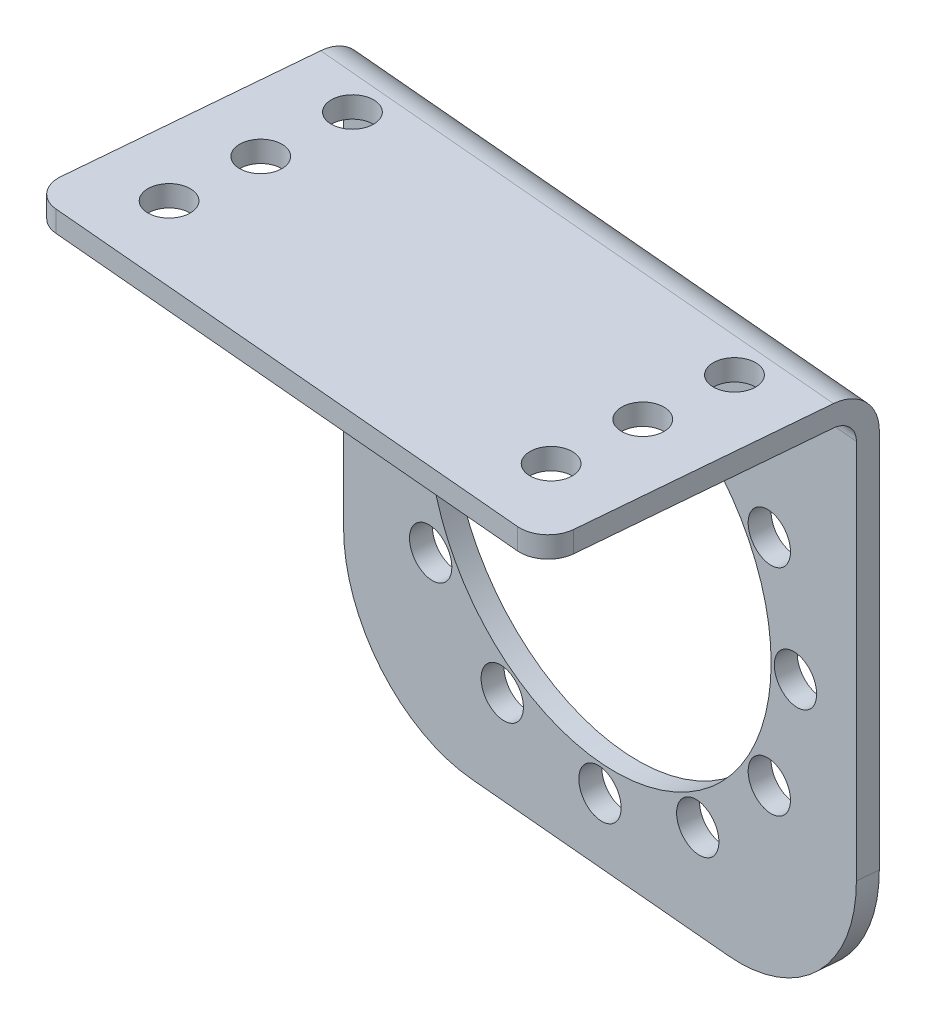
SolidWorks part; units mm, degrees
ref_plane "Front Plane" through (0, 0, 0) normal (0, 0, 1) x (1, 0, 0)
ref_plane "Top Plane" through (0, 0, 0) normal (0, 1, 0) x (1, 0, 0)
ref_plane "Right Plane" through (0, 0, 0) normal (1, 0, 0) x (0, 0, -1)
ref_plane "Plane1" through (-1.3955, 0, 15.9505) normal (-0.0872, 0, 0.9962) x (0, -1, 0)
sketch "Sketch1" plane through (-1.3955, 0, 15.9505) normal (-0.0872, 0, 0.9962) x (0, -1, 0)
  line L0 (-40.4, -20.2615) -> (-0.4, -20.2615)
  line L1 (-0.4, -20.2615) -> (-0.4, 19.7385)
  line L2 (-0.4, 19.7385) -> (-40.4, 19.7385)
  line L3 (-40.4, 19.7385) -> (-40.4, -20.2615)
extrude "Boss-Extrude1" add sketch "Sketch1" against normal blind 22
sketch "Sketch2" plane through (19.6634, 0, 1.7203) normal (0.9962, 0, 0.0872) x (0.0872, 0, -0.9962)
  line L0 (4.4886, 38.9) -> (-16.0114, 38.9)
  line L1 (-16.0114, 38.9) -> (-16.0114, 0.4)
  line L2 (-16.0114, 0.4) -> (4.4886, 0.4)
  line L3 (4.4886, 0.4) -> (4.4886, 38.9)
extrude "Cut-Extrude1" cut sketch "Sketch2" against normal through all
hole_wizard "M24 Clearance Hole1" positions "Sketch4" profile "Sketch3" hole size "M24" standard "ANSI Metric"
sketch "Sketch4" plane through (0.3912, 0, -4.4715) normal (-0.0872, 0, 0.9962) x (0.9962, 0, 0.0872)
  point P0 (-0.2615, 20.2)
sketch "Sketch3" plane through (0.1307, 20.2, -4.4943) normal (0, 1, 0) x (0.9962, 0, 0.0872)
  line L0 (0, 0) -> (0, 4.973)
  line L1 (0, 4.973) -> (13.35, 4.973)
  line L2 (13.35, 4.973) -> (13.35, 0)
  line L5 (13.35, 0) -> (0, 0)
  line L11 (0, -6.35) -> (0, 107.95) construction
  dimension "Thru Hole Dia." = 26.7
  dimension "Thru Hole Depth" = 4.973
hole_wizard "Ø3.3 (3.3) Diameter Hole1" positions "Sketch6" profile "Sketch5" hole size "Ø3.3" standard "ANSI Metric"
sketch "Sketch6" plane through (0.3912, 0, -4.4715) normal (-0.0872, 0, 0.9962) x (0.9962, 0, 0.0872)
  point P0 (-0.2615, 4.95)
  point P1 (-7.8865, 6.9931)
  point P2 (-13.4684, 12.575)
  point P3 (-15.5115, 20.2)
  point P4 (-13.4684, 27.825)
  point P5 (-7.8865, 33.4069)
  point P6 (-0.2615, 35.45)
  point P7 (7.3635, 33.4069)
  point P8 (12.9454, 27.825)
  point P9 (14.9885, 20.2)
  point P10 (12.9454, 12.575)
  point P11 (7.3635, 6.9931)
sketch "Sketch5" plane through (0.1307, 4.95, -4.4943) normal (0, 1, 0) x (0.9962, 0, 0.0872)
  line L0 (0, 0) -> (0, 4.973)
  line L1 (0, 4.973) -> (1.65, 4.973)
  line L2 (1.65, 4.973) -> (1.65, 0)
  line L5 (1.65, 0) -> (0, 0)
  line L11 (0, -6.35) -> (0, 107.95) construction
  dimension "Thru Hole Dia." = 3.3
  dimension "Thru Hole Depth" = 4.973
hole_wizard "Ø3.0 (3) Diameter Hole1" positions "Sketch8" profile "Sketch7" hole size "Ø3.0" standard "ANSI Metric"
sketch "Sketch8" plane through (0, 38.9, 0) normal (0, -1, 0) x (-1, 0, 0)
  point P0 (-14.6516, -0.4902)
  point P1 (-14.1286, -6.4674)
  point P2 (-13.6057, -12.4446)
  point P3 (15.035, 2.107)
  point P4 (15.558, -3.8702)
  point P5 (16.0809, -9.8473)
sketch "Sketch7" plane through (14.6516, 38.9, 0.4902) normal (1, 0, 0) x (0, 0, -1)
  line L0 (0, 0) -> (0, 1.5)
  line L1 (0, 1.5) -> (1.5, 1.5)
  line L2 (1.5, 1.5) -> (1.5, 0)
  line L5 (1.5, 0) -> (0, 0)
  line L11 (0, -6.35) -> (0, 107.95) construction
  dimension "Thru Hole Dia." = 3
  dimension "Thru Hole Depth" = 1.5
fillet "Fillet1" radius 1.5 1 edges at (0.1307, 38.9, -4.4943)
fillet "Fillet2" radius 2 2 edges at (-21.5799, 39.65, 14.1846) (18.2679, 39.65, 17.6708)
fillet "Fillet3" radius 3 1 edges at (0.2615, 40.4, -5.9886)
fillet "Fillet4" radius 10 2 edges at (-19.7278, 0.4, -6.9846) (20.12, 0.4, -3.4983)
